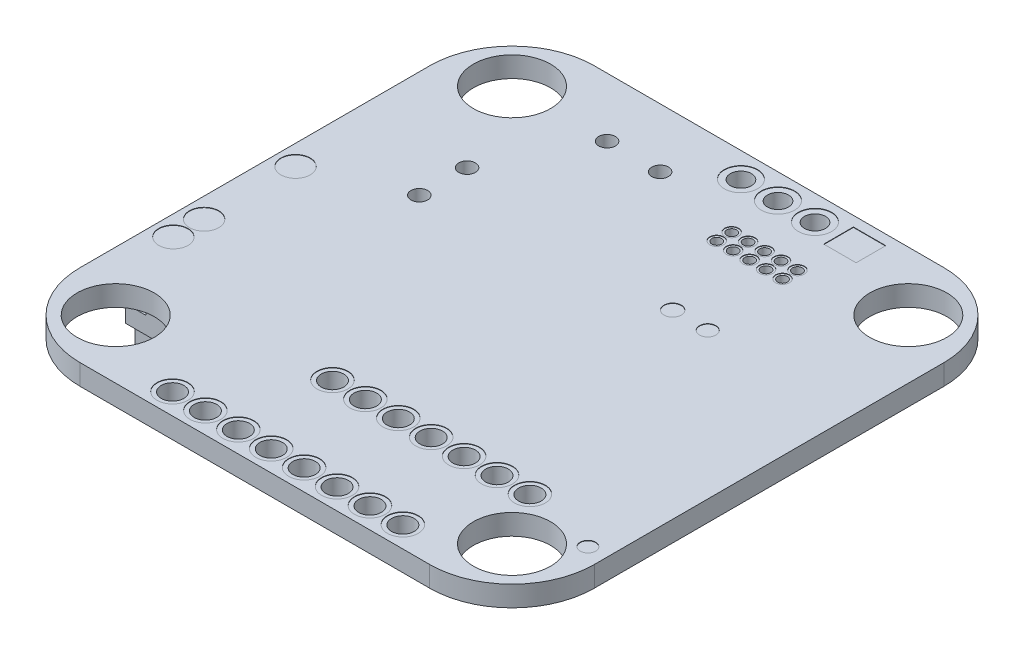
SolidWorks part; units mm, degrees
ref_plane "Front Plane" through (0, 0, 0) normal (0, 0, 1) x (1, 0, 0)
ref_plane "Top Plane" through (0, 0, 0) normal (0, 1, 0) x (1, 0, 0)
ref_plane "Right Plane" through (0, 0, 0) normal (1, 0, 0) x (0, 0, -1)
sketch "Sketch1" plane through (0, 0, 0) normal (0, 1, 0) x (1, 0, 0)
  line L1 (15.875, 15.875) -> (-15.875, 15.875)
  line L2 (15.875, 15.875) -> (15.875, -15.875)
  line L3 (15.875, -15.875) -> (-15.875, -15.875)
  line L4 (-15.875, 15.875) -> (-15.875, -15.875)
  line L5 (15.875, 15.875) -> (-15.875, -15.875) construction
  line L6 (15.875, -15.875) -> (-15.875, 15.875) construction
  point P0 (0, 0)
  dimension "D1" = 31.75
  dimension "D2" = 31.75
extrude "Boss-Extrude1" add sketch "Sketch1" along normal blind 1.27
fillet "Fillet1" radius 5.08 4 edges at (15.875, 0.635, -15.875) (-15.875, 0.635, -15.875) (-15.875, 0.635, 15.875) (15.875, 0.635, 15.875)
sketch "Sketch2" plane through (0, 1.27, 0) normal (0, 1, 0) x (1, 0, 0)
  line L0 (15.875, 0) -> (-15.875, 0) construction
  line L1 (15.875, -10.795) -> (15.875, 10.795) construction
  line L2 (-15.875, 10.795) -> (-15.875, -10.795) construction
  line L3 (0, 0) -> (0, 15.875) construction
  line L4 (10.795, 15.875) -> (-10.795, 15.875) construction
  line L5 (14.3871, 14.3871) -> (0, 0) construction
  arc A0 (15.875, 10.795) -> (10.795, 15.875) centre (10.795, 10.795) ccw construction
  circle A1 centre (12.2354, 12.2354) radius 2.3813
  circle A2 centre (-12.2354, 12.2354) radius 2.3813
  circle A3 centre (-12.2354, -12.2354) radius 2.3813
  circle A4 centre (12.2354, -12.2354) radius 2.3813
  circle A5 centre (-6.3651, 12.2354) radius 0.5132
  circle A6 centre (-3.0883, 12.2354) radius 0.5132
  circle A7 centre (-9.2733, 6.4988) radius 0.5132
  circle A8 centre (-9.2733, 3.5497) radius 0.5132
  dimension "D1" = 4.7625
extrude "Cut-Extrude1" cut sketch "Sketch2" against normal blind 2540
sketch "Sketch6" plane through (0, 1.27, 0) normal (0, 1, 0) x (1, 0, 0)
  line L1 (7.8249, 13.4231) -> (5.8271, 13.4231)
  line L2 (7.8249, 13.4231) -> (7.8249, 15.2545)
  line L3 (7.8249, 15.2545) -> (5.8271, 15.2545)
  line L4 (5.8271, 13.4231) -> (5.8271, 15.2545)
  circle A0 centre (4.3703, 14.3388) radius 1.028
  circle A1 centre (2.0843, 14.3388) radius 1.028
  circle A2 centre (-0.2017, 14.3388) radius 1.028
  circle A3 centre (6.4098, 11.2171) radius 0.4263
  circle A4 centre (6.4098, 10.2934) radius 0.4263
  circle A5 centre (5.3938, 11.2171) radius 0.4263
  circle A6 centre (5.3938, 10.2934) radius 0.4263
  circle A7 centre (4.3778, 11.2171) radius 0.4263
  circle A8 centre (4.3778, 10.2934) radius 0.4263
  circle A9 centre (3.3618, 11.2171) radius 0.4263
  circle A10 centre (3.3618, 10.2934) radius 0.4263
  circle A11 centre (2.3458, 11.2171) radius 0.4263
  circle A12 centre (2.3458, 10.2934) radius 0.4263
  circle A13 centre (-14.6347, 1.2695) radius 0.9051
  circle A14 centre (-14.6347, -4.3754) radius 0.9051
  circle A15 centre (-14.6347, -6.2731) radius 0.9051
  circle A16 centre (6.8557, 5.2299) radius 0.5046
  circle A17 centre (4.6914, 5.2299) radius 0.5345
  circle A18 centre (14.7259, -10.0382) radius 0.4787
  circle A19 centre (10.1218, -9.0151) radius 0.9522
  circle A20 centre (8.0898, -9.0151) radius 0.9522
  circle A21 centre (6.0578, -9.0151) radius 0.9522
  circle A22 centre (4.0258, -9.0151) radius 0.9522
  circle A23 centre (1.9938, -9.0151) radius 0.9522
  circle A24 centre (-0.0382, -9.0151) radius 0.9522
  circle A25 centre (-2.0702, -9.0151) radius 0.9522
  circle A26 centre (7.8249, -14.5636) radius 0.9522
  circle A27 centre (5.7929, -14.5636) radius 0.9522
  circle A28 centre (3.7609, -14.5636) radius 0.9522
  circle A29 centre (1.7289, -14.5636) radius 0.9522
  circle A30 centre (-0.3031, -14.5636) radius 0.9522
  circle A31 centre (-2.3351, -14.5636) radius 0.9522
  circle A32 centre (-4.3671, -14.5636) radius 0.9522
  circle A33 centre (-6.3991, -14.5636) radius 0.9522
  dimension "D1" = 3
  dimension "D2" = 5
  dimension "D3" = 7
  dimension "D4" = 8
extrude "Cut-Extrude2" cut sketch "Sketch6" against normal blind 0.0254
sketch "Sketch7" plane through (0, 0, 0) normal (0, -1, 0) x (1, 0, 0)
  line L1 (12.5906, 7.0757) -> (-2.1435, 7.0757)
  line L2 (12.5906, 7.0757) -> (12.5906, -8.7822)
  line L3 (12.5906, -8.7822) -> (-2.1435, -8.7822)
  line L4 (-2.1435, 7.0757) -> (-2.1435, -8.7822)
  line L5 (-10.8009, -1.4151) -> (-15.379, -1.4151)
  line L6 (-10.8009, -1.4151) -> (-10.8009, -8.7822)
  line L7 (-10.8009, -8.7822) -> (-15.379, -8.7822)
  line L8 (-15.379, -1.4151) -> (-15.379, -8.7822)
extrude "Boss-Extrude5" add sketch "Sketch7" along normal blind 1.905
sketch "Sketch8" plane through (12.5906, 0, 0) normal (1, 0, 0) x (0, 0, -1)
  line L1 (-6.6081, -0.2398) -> (8.2748, -0.2398)
  line L2 (-6.6081, -0.2398) -> (-6.6081, -1.6198)
  line L3 (-6.6081, -1.6198) -> (8.2748, -1.6198)
  line L4 (8.2748, -0.2398) -> (8.2748, -1.6198)
extrude "Cut-Extrude3" cut sketch "Sketch8" against normal blind 13.97
sketch "Sketch10" plane through (-15.379, 0, 0) normal (-1, 0, 0) x (0, 0, 1)
  line L1 (-1.6982, -1.5672) -> (-8.497, -1.5672)
  line L2 (-1.6982, -1.5672) -> (-1.6982, -0.2327)
  line L3 (-1.6982, -0.2327) -> (-8.497, -0.2327)
  line L4 (-8.497, -1.5672) -> (-8.497, -0.2327)
extrude "Cut-Extrude4" cut sketch "Sketch10" against normal blind 3.81
sketch "Sketch11" plane through (0, -1.905, 0) normal (0, -1, 0) x (1, 0, 0)
  line L0 (12.5906, 3.9734) -> (7.7579, 1.1034)
  line L1 (12.5906, -8.7822) -> (12.5906, 7.0757) construction
  line L2 (7.7579, 1.1034) -> (7.7579, -5.7178)
  line L3 (7.7579, -5.7178) -> (12.5906, -7.6037)
  line L4 (12.5906, -7.6037) -> (12.5906, 3.9734)
extrude "Cut-Extrude5" cut sketch "Sketch11" against normal blind 1.27
sketch "Sketch12" plane through (0, -0.2398, 0) normal (0, -1, 0) x (1, 0, 0)
  line L1 (6.4722, 0.5411) -> (3.4338, 0.5411)
  line L2 (6.4722, 0.5411) -> (6.4722, -3.2881)
  line L3 (6.4722, -3.2881) -> (3.4338, -3.2881)
  line L4 (3.4338, 0.5411) -> (3.4338, -3.2881)
  line L5 (6.4722, -3.8292) -> (3.4338, -3.8292)
  line L6 (6.4722, -3.8292) -> (6.4722, -7.8249)
  line L7 (6.4722, -7.8249) -> (3.4338, -7.8249)
  line L8 (3.4338, -3.8292) -> (3.4338, -7.8249)
extrude "Cut-Extrude6" cut sketch "Sketch12" against normal blind 1.27
sketch "Sketch13" plane through (0, -0.2398, 0) normal (0, -1, 0) x (1, 0, 0)
  line L0 (12.5906, -8.2748) -> (12.5906, 6.6081) construction
  line L1 (12.5906, 1.9979) -> (10.9258, 1.9979)
  line L2 (12.5906, 1.9979) -> (12.5906, -7.6584)
  line L3 (12.5906, -7.6584) -> (10.9258, -7.6584)
  line L4 (10.9258, 1.9979) -> (10.9258, -7.6584)
extrude "Cut-Extrude7" cut sketch "Sketch13" against normal up to surface (0.2398 mm away) up to face at (-12.2354, 0, -14.6166)
sketch "Sketch14" plane through (0, -1.905, 0) normal (0, -1, 0) x (1, 0, 0)
  line L0 (-10.8009, -8.7822) -> (-10.8009, -1.4151) construction
  line L1 (-10.8009, -2.7054) -> (-12.2161, -2.7054)
  line L2 (-10.8009, -2.7054) -> (-10.8009, -4.1622)
  line L3 (-10.8009, -4.1622) -> (-12.2161, -4.1622)
  line L4 (-12.2161, -2.7054) -> (-12.2161, -4.1622)
  line L6 (-10.8009, -6.2017) -> (-12.2161, -6.2017)
  line L7 (-10.8009, -6.2017) -> (-10.8009, -7.8249)
  line L8 (-10.8009, -7.8249) -> (-12.2161, -7.8249)
  line L9 (-12.2161, -6.2017) -> (-12.2161, -7.8249)
  line L10 (-13.3398, -2.2892) -> (-14.8799, -2.2892)
  line L11 (-13.3398, -2.2892) -> (-13.3398, -3.1216)
  line L12 (-13.3398, -3.1216) -> (-14.8799, -3.1216)
  line L13 (-14.8799, -2.2892) -> (-14.8799, -3.1216)
  line L14 (-13.3398, -7.1174) -> (-14.8799, -7.1174)
  line L15 (-13.3398, -7.1174) -> (-13.3398, -8.1163)
  line L16 (-13.3398, -8.1163) -> (-14.8799, -8.1163)
  line L17 (-14.8799, -7.1174) -> (-14.8799, -8.1163)
extrude "Cut-Extrude8" cut sketch "Sketch14" against normal blind 1.27
sketch "Sketch15" plane through (0, 0, 0) normal (0, -1, 0) x (-1, 0, 0)
  line L0 (9.3025, -1.7065) -> (9.3025, -0.9646)
  line L1 (15.4612, -8.4144) -> (9.3025, -8.4144)
  line L2 (15.4612, -8.4144) -> (15.4612, -0.9646)
  line L3 (15.4612, -0.9646) -> (9.3025, -0.9646)
  line L4 (9.3025, -8.4144) -> (9.3025, -7.7001)
  line L5 (9.3025, -7.7001) -> (10.8841, -7.7001)
  line L7 (9.3025, -1.7065) -> (10.8841, -1.7065)
  line L8 (10.8841, -7.7001) -> (10.8841, -1.7065)
extrude "Boss-Extrude6" add sketch "Sketch15" along normal blind 4.572
sketch "Sketch16" plane through (-15.4612, 0, 0) normal (-1, 0, 0) x (0, 0, 1)
  line L0 (5.235, -3.8269) -> (7.4617, -3.8269)
  line L1 (1.9941, -0.868) -> (7.4617, -0.868)
  line L2 (1.9941, -0.868) -> (1.9941, -3.8269)
  line L3 (1.9941, -3.8269) -> (4.1499, -3.8269)
  line L4 (7.4617, -0.868) -> (7.4617, -3.8269)
  line L6 (4.1499, -3.8269) -> (4.1499, -4.2647)
  line L7 (4.1499, -4.2647) -> (5.235, -4.2647)
  line L8 (5.235, -3.8269) -> (5.235, -4.2647)
  line L9 (2.9362, -2.6832) -> (3.6166, -2.6832)
  line L10 (2.9362, -2.6832) -> (2.9362, -3.1245)
  line L11 (2.9362, -3.1245) -> (3.6166, -3.1245)
  line L12 (3.6166, -2.6832) -> (3.6166, -3.1245)
  line L13 (5.8786, -2.6832) -> (6.5223, -2.6832)
  line L14 (5.8786, -2.6832) -> (5.8786, -3.1245)
  line L15 (5.8786, -3.1245) -> (6.5223, -3.1245)
  line L16 (6.5223, -2.6832) -> (6.5223, -3.1245)
  line L17 (0.9646, -4.572) -> (0.9646, 0) construction
  line L18 (0.9646, -2.6832) -> (1.5202, -2.6832)
  line L19 (0.9646, -2.6832) -> (0.9646, -3.1245)
  line L20 (0.9646, -3.1245) -> (1.5202, -3.1245)
  line L21 (1.5202, -2.6832) -> (1.5202, -3.1245)
  line L22 (8.4144, -4.572) -> (8.4144, 0) construction
  line L23 (8.4144, -3.1245) -> (7.8096, -3.1245)
  line L24 (8.4144, -3.1245) -> (8.4144, -2.6832)
  line L25 (8.4144, -2.6832) -> (7.8096, -2.6832)
  line L26 (7.8096, -3.1245) -> (7.8096, -2.6832)
extrude "Cut-Extrude9" cut sketch "Sketch16" against normal blind 4.572
sketch "Sketch17" plane through (-15.4612, 0, 0) normal (-1, 0, 0) x (0, 0, 1)
  line L0 (8.4144, -4.572) -> (8.4144, -3.1245) construction
  line L1 (0.9646, -3.1245) -> (1.5202, -3.1245)
  line L2 (0.9646, -3.1245) -> (0.9646, -3.8594)
  line L3 (0.9646, -3.8594) -> (1.5202, -3.8594)
  line L4 (1.5202, -3.1245) -> (1.5202, -3.8594)
  line L5 (7.8096, -3.1245) -> (8.4144, -3.1245)
  line L6 (7.8096, -3.1245) -> (7.8096, -3.8594)
  line L7 (7.8096, -3.8594) -> (8.4144, -3.8594)
  line L8 (8.4144, -3.1245) -> (8.4144, -3.8594)
extrude "Cut-Extrude10" cut sketch "Sketch17" against normal blind 3.048
sketch "Sketch18" plane through (-15.4612, 0, 0) normal (-1, 0, 0) x (0, 0, 1)
  line L0 (8.4144, -4.572) -> (0.9646, -4.572) construction
  line L1 (0.9646, -3.8594) -> (1.5202, -3.8594)
  line L2 (0.9646, -3.8594) -> (0.9646, -4.572)
  line L3 (0.9646, -4.572) -> (1.5202, -4.572)
  line L4 (1.5202, -3.8594) -> (1.5202, -4.572)
  line L5 (0.9646, -2.6832) -> (0.9646, 0) construction
  line L6 (7.8096, -3.8594) -> (8.4144, -3.8594)
  line L7 (7.8096, -3.8594) -> (7.8096, -4.572)
  line L8 (7.8096, -4.572) -> (8.4144, -4.572)
  line L9 (8.4144, -3.8594) -> (8.4144, -4.572)
  line L10 (0.9646, -1.6286) -> (1.5202, -1.6286)
  line L11 (0.9646, -1.6286) -> (0.9646, 0)
  line L12 (0.9646, 0) -> (1.5202, 0)
  line L13 (1.5202, -1.6286) -> (1.5202, 0)
  line L14 (8.4144, 0) -> (0.9646, 0) construction
  line L15 (8.4144, -2.6832) -> (8.4144, 0) construction
  line L16 (8.4144, -1.6286) -> (7.8096, -1.6286)
  line L17 (8.4144, -1.6286) -> (8.4144, 0)
  line L18 (8.4144, 0) -> (7.8096, 0)
  line L19 (7.8096, -1.6286) -> (7.8096, 0)
extrude "Cut-Extrude11" cut sketch "Sketch18" against normal blind 1.27
sketch "Sketch21" plane through (0, 1.2446, 0) normal (0, 1, 0) x (1, 0, 0)
  circle A3 centre (-6.3991, -14.5636) radius 0.6982
  circle A4 centre (-6.3991, -14.5636) radius 0.6982
  circle A6 centre (-4.3671, -14.5636) radius 0.6982
  circle A7 centre (-4.3671, -14.5636) radius 0.6982
  circle A8 centre (-0.3031, -14.5636) radius 0.6982
  circle A9 centre (-2.3351, -14.5636) radius 0.6982
  circle A10 centre (-2.3351, -14.5636) radius 0.6982
  circle A11 centre (1.7289, -14.5636) radius 0.6982
  circle A12 centre (3.7609, -14.5636) radius 0.6982
  circle A13 centre (5.7929, -14.5636) radius 0.6982
  circle A14 centre (7.8249, -14.5636) radius 0.6982
  circle A16 centre (-0.0382, -9.0151) radius 0.6982
  circle A17 centre (-2.0702, -9.0151) radius 0.6982
  circle A18 centre (-2.0702, -9.0151) radius 0.6982
  circle A19 centre (1.9938, -9.0151) radius 0.6982
  circle A20 centre (4.0258, -9.0151) radius 0.6982
  circle A21 centre (6.0578, -9.0151) radius 0.6982
  circle A22 centre (8.0898, -9.0151) radius 0.6982
  circle A23 centre (10.1218, -9.0151) radius 0.6982
  circle A24 centre (4.3703, 14.3388) radius 0.649
  circle A25 centre (2.0843, 14.3388) radius 0.649
  circle A26 centre (-0.2017, 14.3388) radius 0.649
  circle A27 centre (6.4098, 11.2171) radius 0.3016
  circle A28 centre (6.4098, 10.2934) radius 0.3016
  circle A29 centre (5.3938, 11.2171) radius 0.3016
  circle A30 centre (5.3938, 10.2934) radius 0.3016
  circle A31 centre (4.3778, 11.2171) radius 0.3016
  circle A32 centre (4.3778, 10.2934) radius 0.3016
  circle A33 centre (3.3618, 11.2171) radius 0.3016
  circle A34 centre (3.3618, 10.2934) radius 0.3016
  circle A35 centre (2.3458, 11.2171) radius 0.3016
  circle A36 centre (2.3458, 10.2934) radius 0.3016
  dimension "D1" = 0.254
  dimension "D2" = 0.254
  dimension "D3" = 0.254
  dimension "D5" = 0.254
  dimension "D4" = 6
  dimension "D6" = 7
  dimension "D7" = 3
  dimension "D8" = 5
extrude "Cut-Extrude12" cut sketch "Sketch21" against normal blind 16.002
